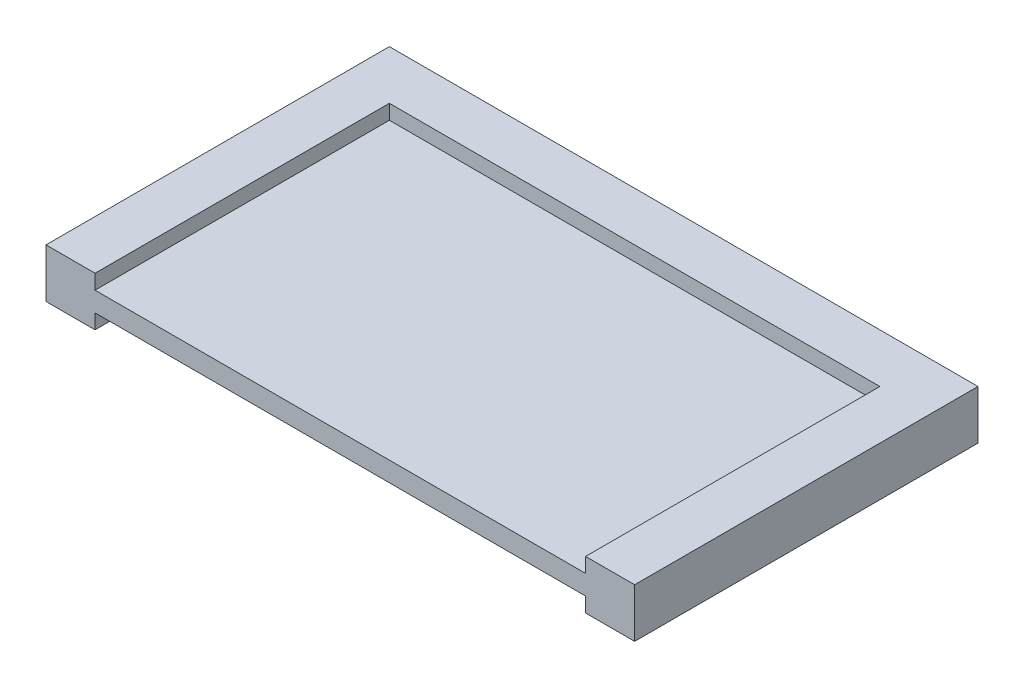
SolidWorks part; units mm, degrees
ref_plane "Front Plane" through (0, 0, 0) normal (0, 0, 1) x (1, 0, 0)
ref_plane "Top Plane" through (0, 0, 0) normal (0, 1, 0) x (1, 0, 0)
ref_plane "Right Plane" through (0, 0, 0) normal (1, 0, 0) x (0, 0, -1)
sketch "Sketch1" plane through (0, 0, 0) normal (0, 1, 0) x (1, 0, 0)
  line L0 (-19.05, 0) -> (-15.875, 0)
  line L1 (-15.875, 0) -> (-15.875, 19.05)
  line L2 (-15.875, 19.05) -> (15.875, 19.05)
  line L3 (0, 19.05) -> (0, 22.225) construction
  line L4 (19.05, 22.225) -> (-19.05, 22.225)
  line L5 (-19.05, 22.225) -> (-19.05, 0)
  line L6 (19.05, 22.225) -> (19.05, 0)
  line L7 (15.875, 0) -> (15.875, 19.05)
  line L8 (19.05, 0) -> (15.875, 0)
  dimension "D1" = 19.05
  dimension "D2" = 3.175
  dimension "D3" = 22.225
extrude "Boss-Extrude1" add sketch "Sketch1" along normal mid plane 3.175
sketch "Sketch2" plane through (0, 0, 0) normal (0, 1, 0) x (1, 0, 0)
  line L0 (15.875, 0) -> (19.05, 0) construction
  line L1 (-15.875, 19.05) -> (15.875, 19.05)
  line L2 (-15.875, 19.05) -> (-15.875, 0)
  line L3 (-15.875, 0) -> (15.875, 0)
  line L4 (15.875, 19.05) -> (15.875, 0)
  line L5 (15.875, 19.05) -> (15.875, 0) construction
extrude "Boss-Extrude2" add sketch "Sketch2" along normal mid plane 1.27
